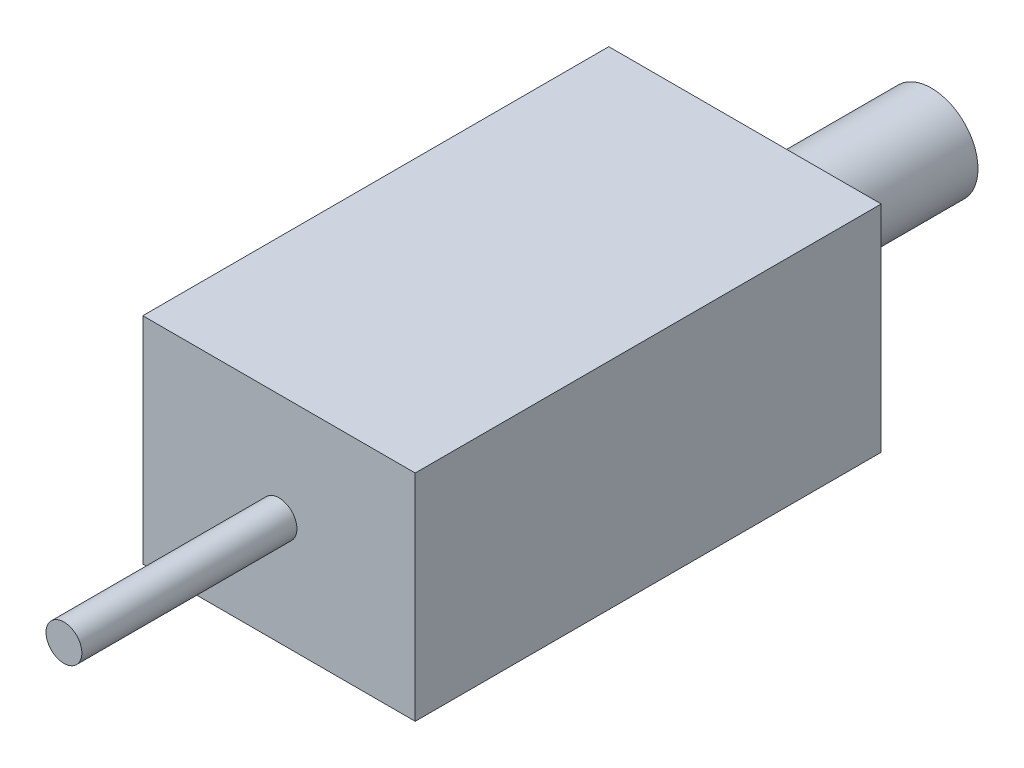
SolidWorks part; units mm, degrees
ref_plane "Front Plane" through (0, 0, 0) normal (0, 0, 1) x (1, 0, 0)
ref_plane "Top Plane" through (0, 0, 0) normal (0, 1, 0) x (1, 0, 0)
ref_plane "Right Plane" through (0, 0, 0) normal (1, 0, 0) x (0, 0, -1)
sketch "Sketch1" plane through (0, 0, 0) normal (0, 0, 1) x (1, 0, 0)
  line L1 (-19, -15) -> (19, -15)
  line L2 (-19, -15) -> (-19, 15)
  line L3 (-19, 15) -> (19, 15)
  line L4 (19, -15) -> (19, 15)
  line L5 (-19, -15) -> (19, 15) construction
  line L6 (-19, 15) -> (19, -15) construction
  point P0 (0, 0)
  dimension "D1" = 30
  dimension "D2" = 38
extrude "Boss-Extrude1" add sketch "Sketch1" along normal blind 65
sketch "Sketch2" plane through (0, 0, 65) normal (0, 0, 1) x (1, 0, 0)
  circle A0 centre (0, 0) radius 2.5
  dimension "D1" = 5
extrude "Boss-Extrude2" add sketch "Sketch2" along normal blind 30
sketch "Sketch3" plane through (0, 0, 0) normal (0, 0, -1) x (-1, 0, 0)
  circle A0 centre (0, 0) radius 6.5
  dimension "D1" = 13
extrude "Boss-Extrude3" add sketch "Sketch3" along normal blind 26
